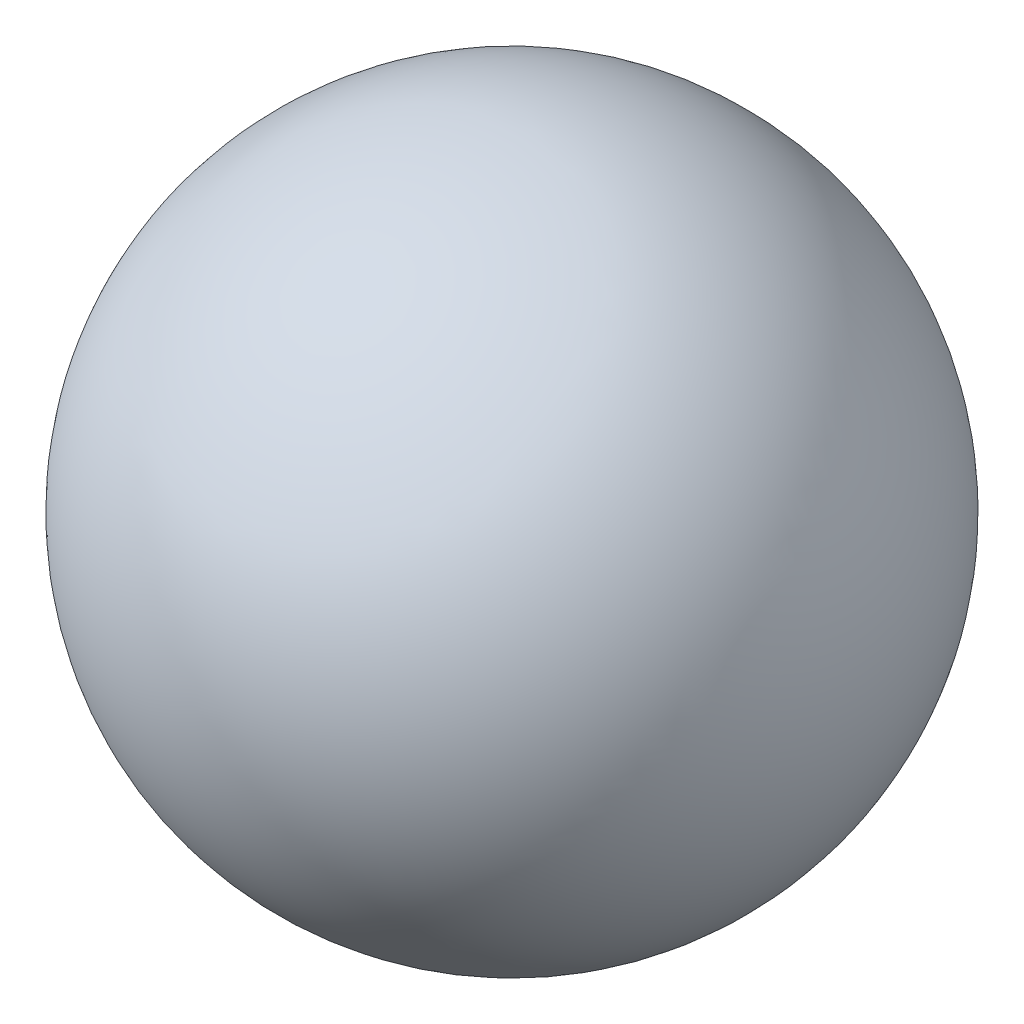
SolidWorks part; units mm, degrees
ref_plane "Спереди" through (0, 0, 0) normal (0, 0, 1) x (1, 0, 0)
ref_plane "Сверху" through (0, 0, 0) normal (0, 1, 0) x (1, 0, 0)
ref_plane "Справа" through (0, 0, 0) normal (1, 0, 0) x (0, 0, -1)
sketch "Эскиз1" plane through (0, 0, 0) normal (0, 0, 1) x (1, 0, 0)
  line L0 (-5, 0) -> (5, 0) construction
  line L1 (-5, 0) -> (5, 0)
  arc A0 (-5, 0) -> (5, 0) centre (0, 0) cw
  dimension "D1" = 10
revolve "Повернуть1" add sketch "Эскиз1" angle 360 about L0
sketch "Эскиз2" plane through (0, 0, 0) normal (0, 0, 1) x (1, 0, 0)
  line L0 (-10, 0) -> (10, 0) construction
  line L1 (-10, 0) -> (10, 0)
  arc A0 (-10, 0) -> (10, 0) centre (0, 0) cw
  dimension "D1" = 20
revolve "Повернуть2" add sketch "Эскиз2" angle 360 about L0
equation "\"Площадь в метрах квадратных\"= \"Площадь\" / 1000000"
